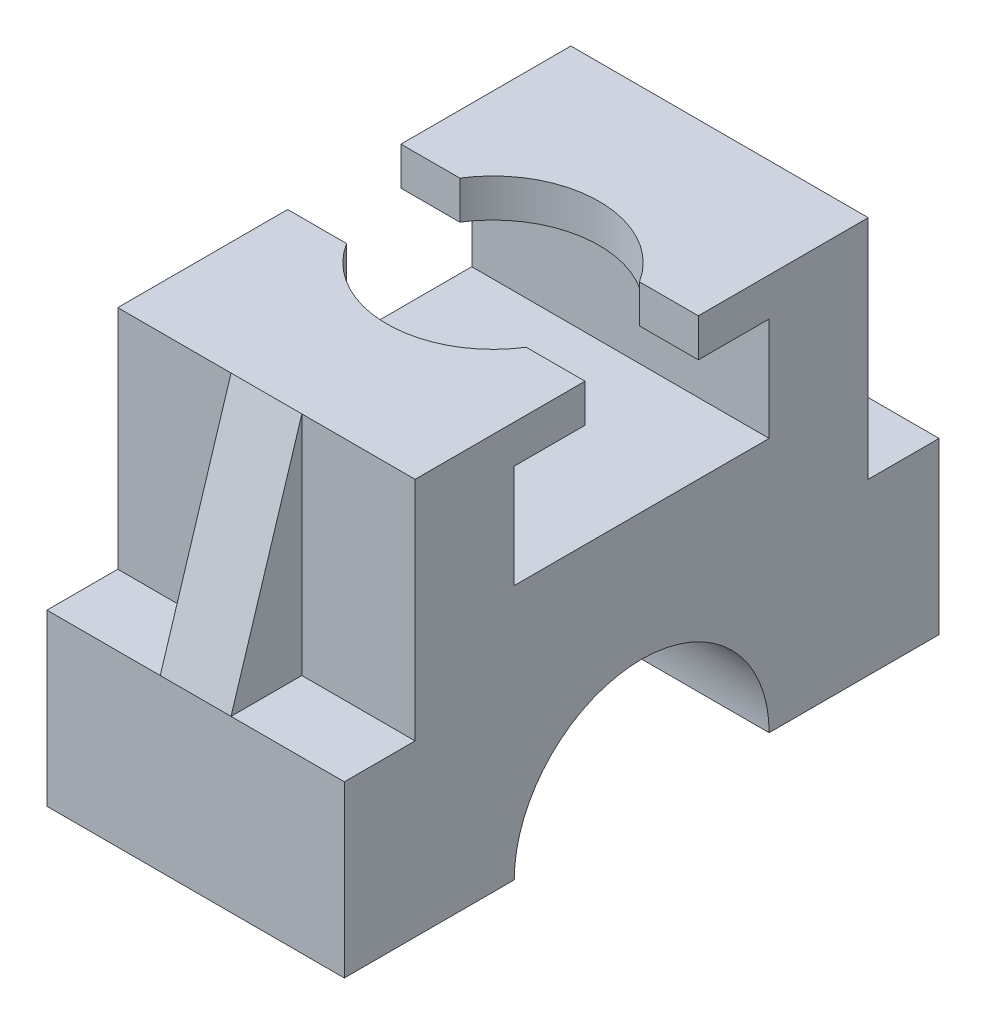
SolidWorks part; units mm, degrees
ref_plane "Front Plane" through (0, 0, 0) normal (0, 0, 1) x (1, 0, 0)
ref_plane "Top Plane" through (0, 0, 0) normal (0, 1, 0) x (1, 0, 0)
ref_plane "Right Plane" through (0, 0, 0) normal (1, 0, 0) x (0, 0, -1)
sketch "Sketch1" plane through (0, 0, 0) normal (1, 0, 0) x (0, 0, -1)
  line L0 (45, 0) -> (105, 0)
  line L1 (105, 0) -> (105, 60)
  line L2 (105, 60) -> (80, 60)
  line L3 (80, 140) -> (80, 60)
  line L4 (80, 140) -> (20, 140)
  line L5 (20, 140) -> (20, 126.5217)
  line L6 (20, 126.5217) -> (45, 126.5217)
  line L7 (45, 126.5217) -> (45, 90)
  line L8 (45, 90) -> (-45, 90)
  line L9 (0, 0) -> (0, 60) construction
  line L10 (-45, 126.5217) -> (-45, 90)
  line L11 (-20, 126.5217) -> (-45, 126.5217)
  line L12 (-20, 140) -> (-20, 126.5217)
  line L13 (-80, 140) -> (-20, 140)
  line L14 (-80, 140) -> (-80, 60)
  line L15 (-105, 60) -> (-80, 60)
  line L16 (-105, 0) -> (-105, 60)
  line L17 (-45, 0) -> (-105, 0)
  arc A0 (45, 0) -> (-45, 0) centre (0, 0) ccw
  point P15 (0, 90)
  dimension "D2" = 45
  dimension "D1" = 60
  dimension "D3" = 60
  dimension "D4" = 80
  dimension "D5" = 60
  dimension "D6" = 45
  dimension "D7" = 50
  dimension "D8" = 25
extrude "Boss-Extrude1" add sketch "Sketch1" along normal mid plane 105
sketch "Sketch2" plane through (0, 0, 0) normal (1, 0, 0) x (0, 0, -1)
  line L0 (80, 140) -> (105, 60)
sketch "Sketch3" plane through (0, 0, 0) normal (1, 0, 0) x (0, 0, -1)
  line L0 (-80, 140) -> (-105, 60)
rib "Rib1" sketch "Sketch3" sketch "Sketch3" thickness 25 extrusion direction parallel to sketch draft on no parameters "D1"=25
rib "Rib2" sketch "Sketch2" sketch "Sketch2" thickness 25 extrusion direction parallel to sketch draft on no parameters "D1"=25
sketch "Sketch5" plane through (0, 140, 0) normal (0, 1, 0) x (1, 0, 0)
  line L0 (52.5, -20) -> (-52.5, -20) construction
  line L1 (52.5, 20) -> (-52.5, 20) construction
  line L2 (31.7214, -20) -> (-31.7214, -20)
  line L3 (31.7214, 20) -> (-31.7214, 20)
  arc A0 (-31.7214, -20) -> (31.7214, -20) centre (0, 0) ccw
  arc A1 (31.7214, 20) -> (-31.7214, 20) centre (0, 0) ccw
  dimension "D1" = 75
extrude "Cut-Extrude1" cut sketch "Sketch5" against normal blind 31
